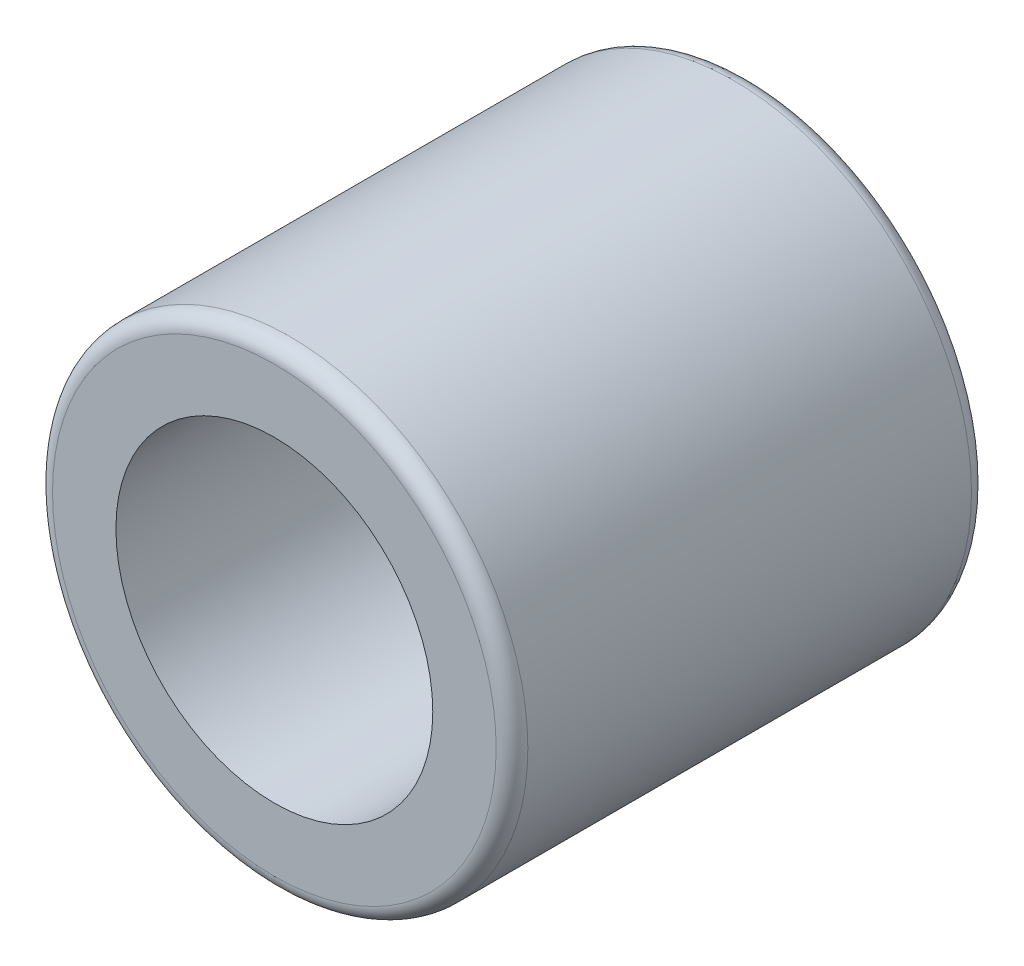
SolidWorks part; units mm, degrees
material "Alloy Steel (SS)"
ref_plane "Front Plane" through (0, 0, 0) normal (0, 0, 1) x (1, 0, 0)
ref_plane "Top Plane" through (0, 0, 0) normal (0, 1, 0) x (1, 0, 0)
ref_plane "Right Plane" through (0, 0, 0) normal (1, 0, 0) x (0, 0, -1)
sketch "Sketch1" plane through (0, 0, 0) normal (0, 0, 1) x (1, 0, 0)
  circle A0 centre (0, 0) radius 15
  circle A1 centre (0, 0) radius 10
extrude "Boss-Extrude1" add sketch "Sketch1" along normal blind 30
fillet "Fillet1" radius 1 2 edges at (15, 0, 30) (15, 0, 0)
